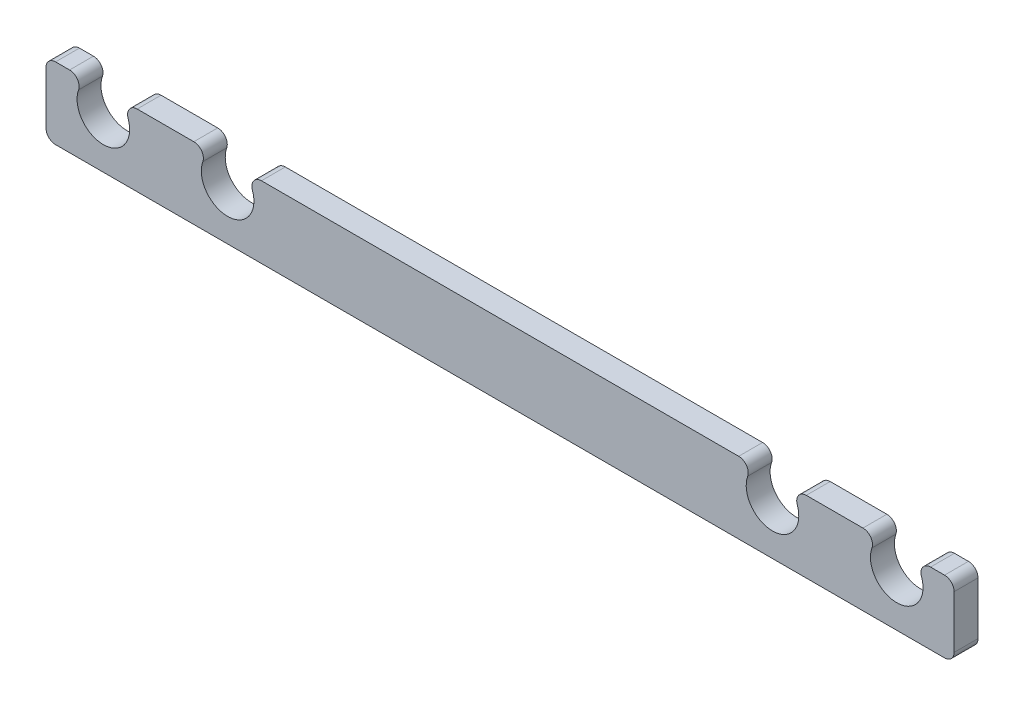
SolidWorks part; units mm, degrees
ref_plane "Plan de face" through (0, 0, 0) normal (0, 0, 1) x (1, 0, 0)
ref_plane "Plan de dessus" through (0, 0, 0) normal (0, 1, 0) x (1, 0, 0)
ref_plane "Plan de droite" through (0, 0, 0) normal (1, 0, 0) x (0, 0, -1)
sketch "Esquisse1" plane through (0, 0, 0) normal (0, 0, 1) x (1, 0, 0)
  line L0 (-95, 0) -> (95, 0) construction
  line L1 (-83, 7.9101) -> (-83, -5.5447) construction
  line L2 (-57, 7.9101) -> (-57, -7.9101) construction
  line L3 (0, 0) -> (0, 30.4365) construction
  line L4 (57, 7.9101) -> (57, -7.9101) construction
  line L5 (83, 7.9101) -> (83, -5.5447) construction
  line L6 (-70, 5.6746) -> (-70, -5.9047) construction
  line L7 (70, 5.6746) -> (70, -5.9047) construction
  line L8 (-83, -4.5) -> (83, -4.5) construction
  line L9 (-79.8377, 0) -> (-60.1623, 0)
  line L10 (-53.8377, 0) -> (53.8377, 0)
  line L11 (60.1623, 0) -> (79.8377, 0)
  line L12 (86.1623, 0) -> (95, 0)
  line L13 (95, 0) -> (95, -15)
  line L14 (95, -15) -> (-95, -15)
  line L15 (-95, -15) -> (-95, 0)
  line L16 (-95, 0) -> (-86.1623, 0)
  arc A0 (-60.1623, 0) -> (-53.8377, 0) centre (-57, -4.5) ccw
  arc A1 (60.1623, 0) -> (53.8377, 0) centre (57, -4.5) cw
  arc A2 (-79.8377, 0) -> (-86.1623, 0) centre (-83, -4.5) cw
  arc A3 (79.8377, 0) -> (86.1623, 0) centre (83, -4.5) ccw
  point P29 (0, 0)
  dimension "D3" = 5.5
  dimension "D1" = 140
  dimension "D2" = 190
  dimension "D4" = 26
  dimension "D5" = 4.5
  dimension "D6" = 6.3246
  dimension "D7" = 15
extrude "Boss.-Extru.1" add sketch "Esquisse1" along normal blind 5
fillet "Congé1" radius 2 12 edges at (-86.1623, 0, 2.5) (-95, -15, 2.5) (-53.8377, 0, 2.5) (-60.1623, 0, 2.5) (-79.8377, 0, 2.5) (-95, 0, 2.5) (95, -15, 2.5) (53.8377, 0, 2.5) (60.1623, 0, 2.5) (79.8377, 0, 2.5) (86.1623, 0, 2.5) (95, 0, 2.5)
